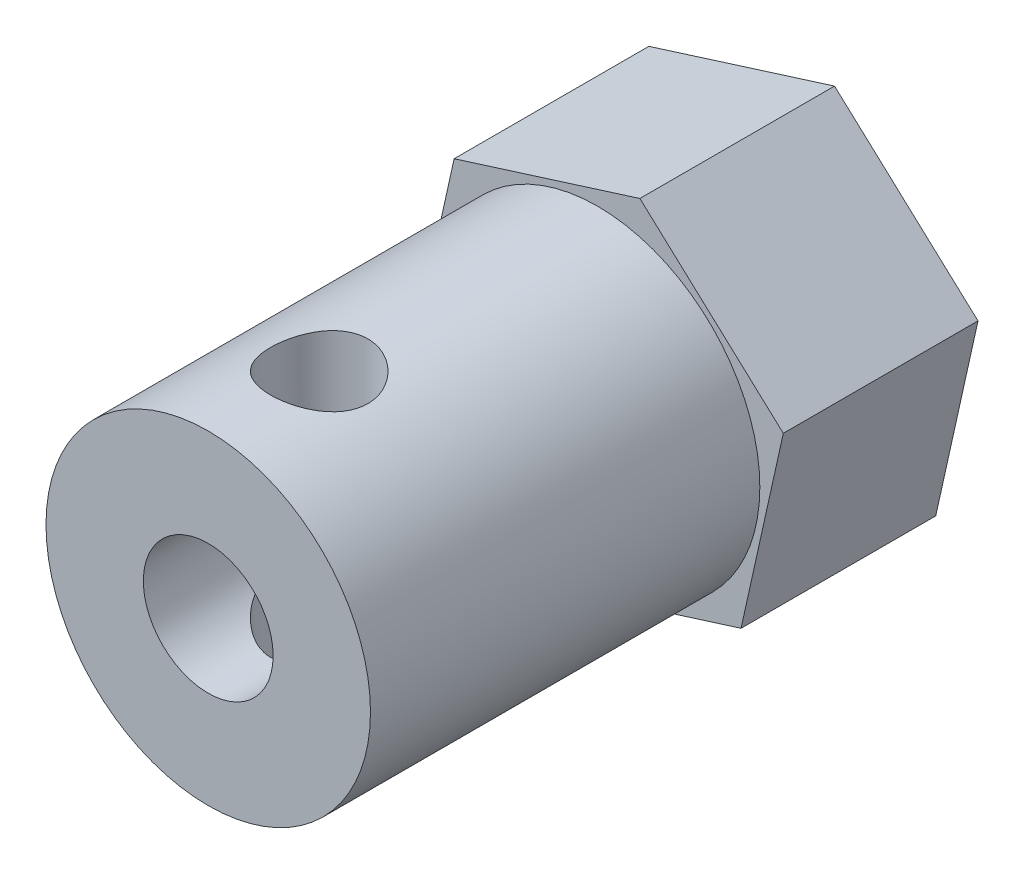
SolidWorks part; units mm, degrees
material "Copper"
ref_plane "Front Plane" through (0, 0, 0) normal (0, 0, 1) x (1, 0, 0)
ref_plane "Top Plane" through (0, 0, 0) normal (0, 1, 0) x (1, 0, 0)
ref_plane "Right Plane" through (0, 0, 0) normal (1, 0, 0) x (0, 0, -1)
sketch "Sketch3" plane through (0, 0, 0) normal (0, 0, 1) x (1, 0, 0)
  line L1 (-4.4209, 4.0565) -> (-5.7235, -1.8003)
  line L2 (-5.7235, -1.8003) -> (-1.3026, -5.8569)
  line L3 (-1.3026, -5.8569) -> (4.4209, -4.0565)
  line L4 (4.4209, -4.0565) -> (5.7235, 1.8003)
  line L5 (5.7235, 1.8003) -> (1.3026, 5.8569)
  line L6 (1.3026, 5.8569) -> (-4.4209, 4.0565)
  circle A0 centre (0, 0) radius 6 construction
  dimension "D1" = 12
extrude "Boss-Extrude2" add sketch "Sketch3" along normal blind 6
sketch "Sketch4" plane through (0, 0, 6) normal (0, 0, 1) x (1, 0, 0)
  circle A0 centre (0, 0) radius 5
  dimension "D1" = 10
extrude "Boss-Extrude3" add sketch "Sketch4" along normal blind 12
sketch "Sketch5" plane through (0, 0, 0) normal (0, 1, 0) x (1, 0, 0)
  circle A0 centre (0, -14.5805) radius 1.5
  dimension "D1" = 3
extrude "Cut-Extrude1" cut sketch "Sketch5" against normal mid plane 12
sketch "Sketch6" plane through (0, 0, 18) normal (0, 0, 1) x (1, 0, 0)
  circle A0 centre (0, 0) radius 2
  dimension "D1" = 4
extrude "Cut-Extrude2" cut sketch "Sketch6" against normal up to surface (12 mm away) up to face at (5, 0, 6)
sketch "Sketch7" plane through (0, 0, 0) normal (0, 0, -1) x (-1, 0, 0)
  circle A0 centre (0, 0) radius 1.5
  dimension "D1" = 3
extrude "Cut-Extrude3" cut sketch "Sketch7" against normal blind 10
